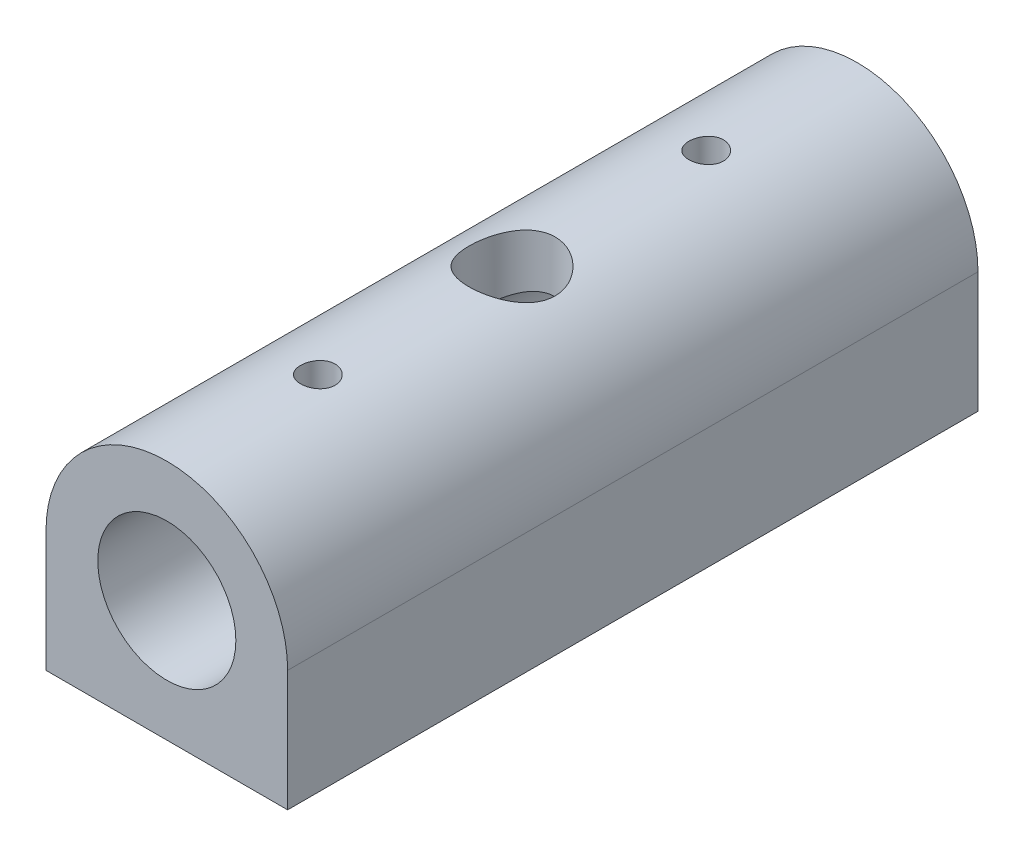
SolidWorks part; units mm, degrees
ref_plane "Front Plane" through (0, 0, 0) normal (0, 0, 1) x (1, 0, 0)
ref_plane "Top Plane" through (0, 0, 0) normal (0, 1, 0) x (1, 0, 0)
ref_plane "Right Plane" through (0, 0, 0) normal (1, 0, 0) x (0, 0, -1)
sketch "Sketch1" plane through (0, 0, 0) normal (0, 0, 1) x (1, 0, 0)
  line L0 (-7, 0) -> (-7, -7)
  line L1 (-7, -7) -> (7, -7)
  line L2 (7, -7) -> (7, 0)
  line L3 (-7, 0) -> (-4, 0) construction
  line L4 (0, -4) -> (0, -7) construction
  circle A0 centre (0, 0) radius 4
  arc A2 (-7, 0) -> (7, 0) centre (0, 0) cw
  point P10 (6.6835, -6.9958)
  dimension "D1" = 8
  dimension "D2" = 3
extrude "Boss-Extrude1" add sketch "Sketch1" along normal mid plane 40
sketch "Sketch2" plane through (0, -7, 0) normal (0, -1, 0) x (-1, 0, 0)
  circle A0 centre (0, 0) radius 2.5
  dimension "D1" = 5
extrude "Cut-Extrude1" cut sketch "Sketch2" against normal through all
sketch "Sketch3" plane through (0, 0, 0) normal (0, 1, 0) x (1, 0, 0)
  line L0 (0, -11.25) -> (0, 11.25) construction
  line L1 (0, 2.5) -> (0, 20) construction
  line L2 (7, 20) -> (-7, 20) construction
  circle A0 centre (0, 0) radius 2.5 construction
  circle A1 centre (0, 11.25) radius 1
  circle A2 centre (0, -11.25) radius 1
  point P11 (0, -12.6713)
  dimension "D1" = 2
extrude "Cut-Extrude2" cut sketch "Sketch3" along normal through all
